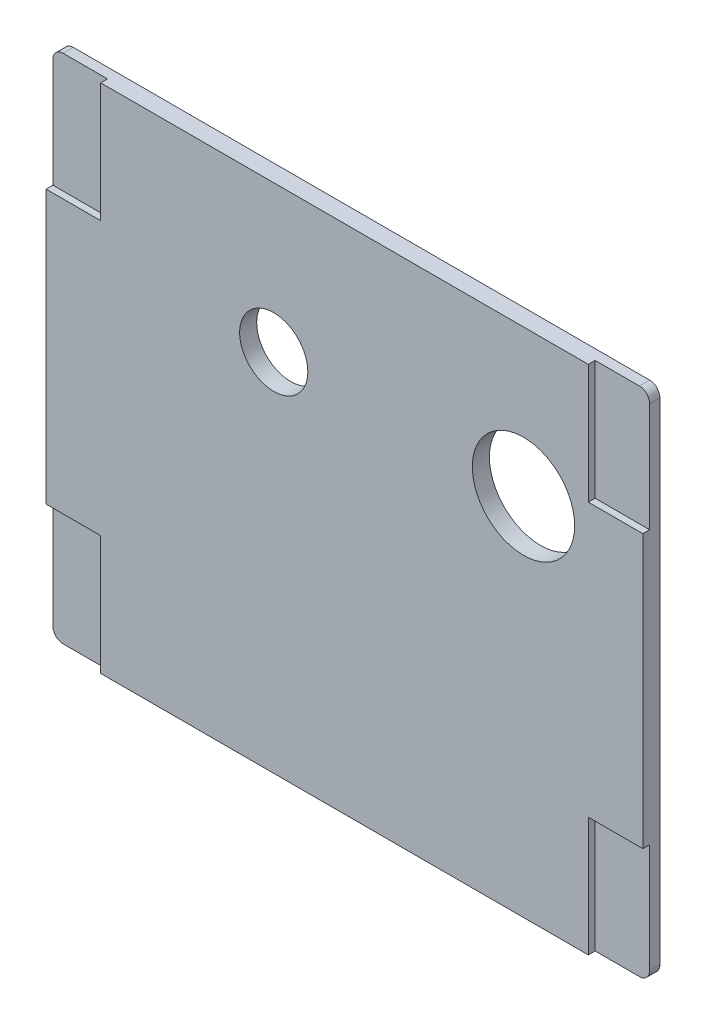
SolidWorks part; units mm, degrees
ref_plane "Front Plane" through (0, 0, 0) normal (0, 0, 1) x (1, 0, 0)
ref_plane "Top Plane" through (0, 0, 0) normal (0, 1, 0) x (1, 0, 0)
ref_plane "Right Plane" through (0, 0, 0) normal (1, 0, 0) x (0, 0, -1)
sketch "Sketch1" plane through (0, 0, 0) normal (0, 0, 1) x (1, 0, 0)
  line L1 (0, 0) -> (-175, 0)
  line L2 (0, 0) -> (0, -150)
  line L3 (0, -150) -> (-175, -150)
  line L4 (-175, 0) -> (-175, -150)
  dimension "D1" = 175
  dimension "D2" = 150
extrude "Boss-Extrude1" add sketch "Sketch1" along normal blind 5
sketch "Sketch3" plane through (0, 0, 5) normal (0, 0, 1) x (1, 0, 0)
  line L1 (0, 0) -> (-175, 0) construction
  line L2 (-175, 0) -> (-175, -150) construction
  line L3 (0, -150) -> (0, 0) construction
  circle A0 centre (-35, -43) radius 15
  circle A1 centre (-108.25, -43) radius 10
  dimension "D1" = 30
  dimension "D2" = 20
  dimension "D3" = 43
  dimension "D4" = 66.75
  dimension "D5" = 43
  dimension "D6" = 35
extrude "Cut-Extrude1" cut sketch "Sketch3" against normal up to surface (5 mm away) up to face at (-87.5, -75, 0)
sketch "Sketch4" plane through (0, 0, 5) normal (0, 0, 1) x (1, 0, 0)
  line L1 (-175, 0) -> (-159, 0)
  line L2 (-175, 0) -> (-175, -35)
  line L3 (-175, -35) -> (-159, -35)
  line L4 (-159, 0) -> (-159, -35)
  line L5 (0, 0) -> (-16, 0)
  line L6 (0, 0) -> (0, -35)
  line L7 (0, -35) -> (-16, -35)
  line L8 (-16, 0) -> (-16, -35)
  line L9 (0, -150) -> (-16, -150)
  line L10 (0, -150) -> (0, -115)
  line L11 (0, -115) -> (-16, -115)
  line L12 (-16, -150) -> (-16, -115)
  line L13 (-175, -150) -> (-159, -150)
  line L14 (-175, -150) -> (-175, -115)
  line L15 (-175, -115) -> (-159, -115)
  line L16 (-159, -150) -> (-159, -115)
  dimension "D1" = 35
  dimension "D2" = 16
extrude "Cut-Extrude2" cut sketch "Sketch4" against normal blind 2
fillet "Fillet1" radius 3 4 edges at (-175, 0, 1.5) (-175, -150, 1.5) (0, -150, 1.5) (0, 0, 1.5)
